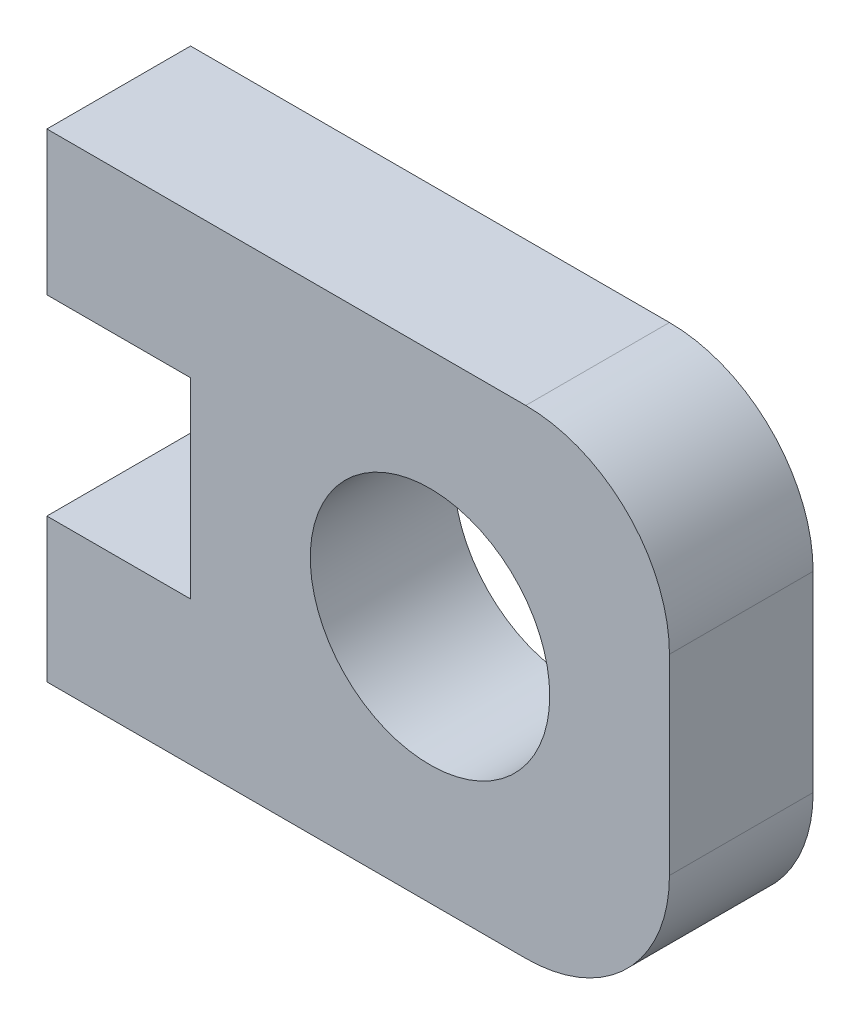
SolidWorks part; units mm, degrees
ref_plane "Front Plane" through (0, 0, 0) normal (0, 0, 1) x (1, 0, 0)
ref_plane "Top Plane" through (0, 0, 0) normal (0, 1, 0) x (1, 0, 0)
ref_plane "Right Plane" through (0, 0, 0) normal (1, 0, 0) x (0, 0, -1)
sketch "Sketch1" plane through (0, 0, 0) normal (0, 0, 1) x (1, 0, 0)
  line L0 (0, 10) -> (10, 10)
  line L1 (10, 0) -> (0, 0)
  line L2 (0, 0) -> (0, 3)
  line L3 (0, 3) -> (3, 3)
  line L6 (0, 10) -> (0, 7)
  line L7 (0, 7) -> (3, 7)
  line L10 (3, 7) -> (3, 3)
  line L12 (13, 7) -> (13, 3)
  arc A0 (10, 0) -> (13, 3) centre (10, 3) ccw
  arc A1 (10, 10) -> (13, 7) centre (10, 7) cw
  circle A2 centre (8, 5) radius 2.5
  point P11 (13, 0)
  point P14 (13, 10)
  dimension "D4" = 3
  dimension "D5" = 5
  dimension "D6" = 5
  dimension "D7" = 5
  dimension "D1" = 13
  dimension "D2" = 10
  dimension "D3" = 3
extrude "Boss-Extrude1" add sketch "Sketch1" along normal blind 3
